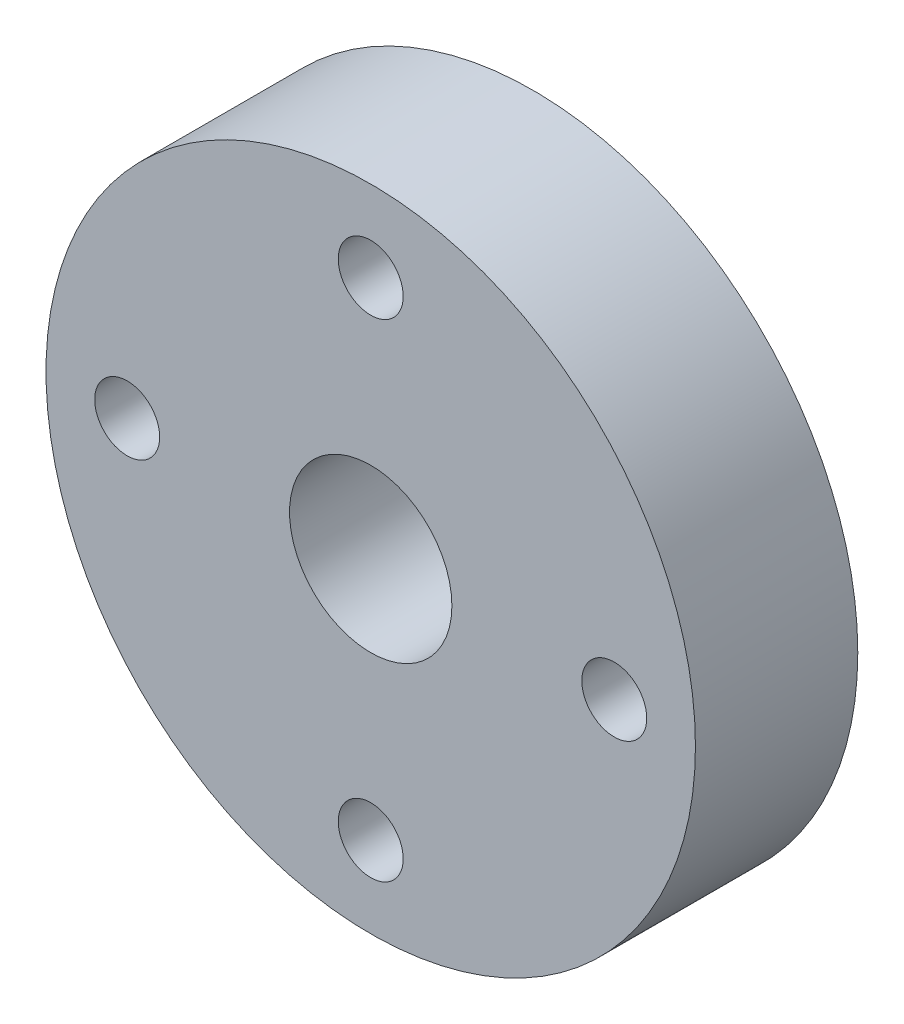
SolidWorks part; units mm, degrees
ref_plane "Front Plane" through (0, 0, 0) normal (0, 0, 1) x (1, 0, 0)
ref_plane "Top Plane" through (0, 0, 0) normal (0, 1, 0) x (1, 0, 0)
ref_plane "Right Plane" through (0, 0, 0) normal (1, 0, 0) x (0, 0, -1)
sketch "Sketch1" plane through (0, 0, 0) normal (0, 0, 1) x (1, 0, 0)
  circle A0 centre (-251.9828, 110.0953) radius 100
  circle A1 centre (-251.9828, 110.0953) radius 75 construction
  circle A2 centre (-251.9828, 185.0953) radius 10
  circle A3 centre (-176.9828, 110.0953) radius 10
  circle A4 centre (-251.9828, 35.0953) radius 10
  circle A5 centre (-326.9828, 110.0953) radius 10
  circle A6 centre (-251.9828, 110.0953) radius 25
  dimension "D1" = 200
  dimension "D2" = 150
  dimension "D3" = 20
  dimension "D4" = 20
  dimension "D5" = 20
  dimension "D6" = 20
  dimension "D7" = 50
extrude "Boss-Extrude2" add sketch "Sketch1" along normal blind 50
